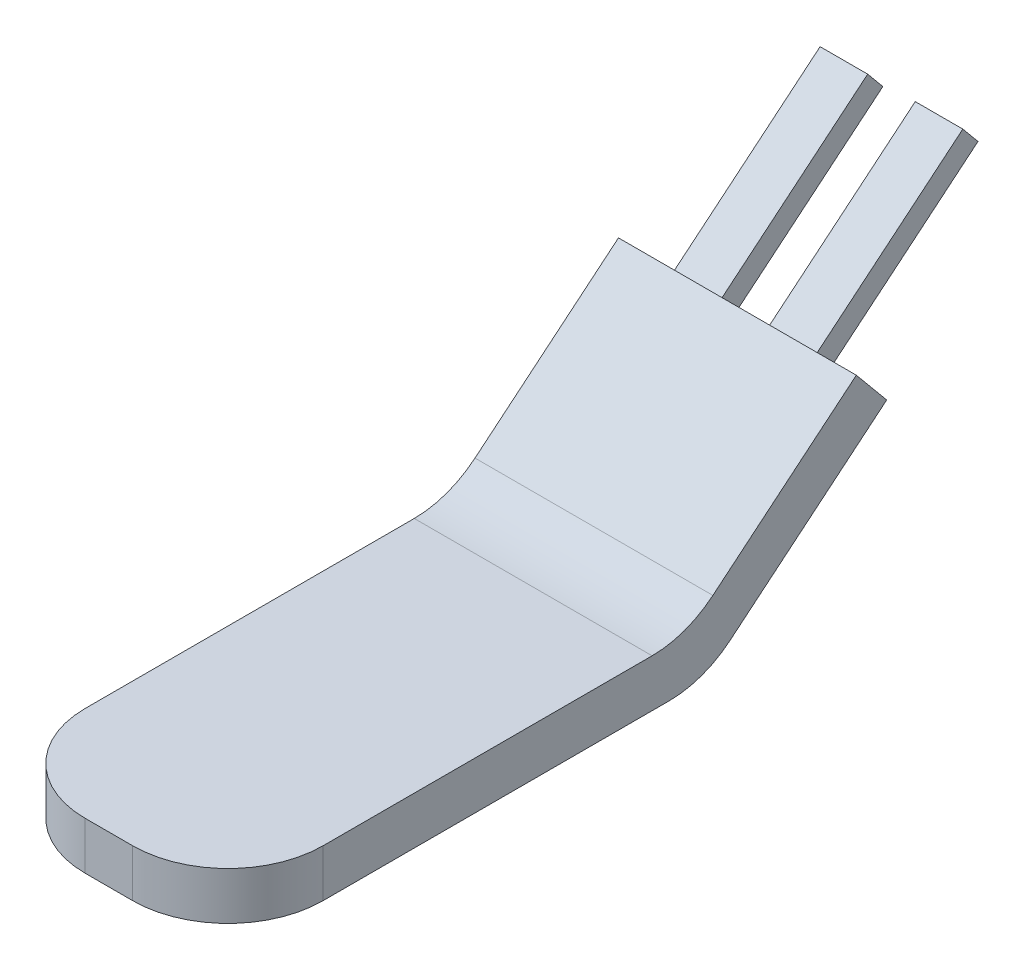
SolidWorks part; units mm, degrees
ref_plane "Front Plane" through (0, 0, 0) normal (0, 0, 1) x (1, 0, 0)
ref_plane "Top Plane" through (0, 0, 0) normal (0, 1, 0) x (1, 0, 0)
ref_plane "Right Plane" through (0, 0, 0) normal (1, 0, 0) x (0, 0, -1)
sketch "Sketch1" plane through (0, 0, 0) normal (1, 0, 0) x (0, 0, -1)
  line L0 (0, 0) -> (5, 0)
  line L1 (5, 0) -> (6.9242, 1.596)
  line L2 (6.9242, 1.596) -> (6.605, 1.9809)
  line L3 (6.605, 1.9809) -> (4.8196, 0.5)
  line L4 (4.8196, 0.5) -> (0, 0.5)
  line L5 (0, 0.5) -> (0, 0)
  dimension "D1" = 0.5
  dimension "D2" = 0.5
  dimension "D3" = 5
  dimension "D4" = 2.5
extrude "Boss-Extrude1" add sketch "Sketch1" along normal blind 2.5
fillet "Fillet1" radius 1 2 edges at (2.5, 0.25, 0) (0, 0.25, 0)
fillet "Fillet2" radius 1 2 edges at (1.25, 0, -5) (1.25, 0.5, -4.8196)
sketch "Sketch3" plane through (0, 4.0529, -4.8864) normal (0, 0.6384, -0.7697) x (-1, 0, 0)
  line L0 (-2.5, -2.9421) -> (0, -2.9421) construction
  line L1 (-2.5, -3.1921) -> (-2.5, -2.6921) construction
  line L2 (0, -3.1921) -> (0, -2.6921) construction
  line L4 (-1.5, -3.0671) -> (-2, -3.0671)
  line L5 (-1.5, -3.0671) -> (-1.5, -2.8171)
  line L6 (-1.5, -2.8171) -> (-2, -2.8171)
  line L7 (-2, -3.0671) -> (-2, -2.8171)
  line L8 (-1.5, -3.0671) -> (-2, -2.8171) construction
  line L9 (-1.5, -2.8171) -> (-2, -3.0671) construction
  line L10 (-1, -3.0671) -> (-0.5, -3.0671)
  line L11 (-1, -3.0671) -> (-1, -2.8171)
  line L12 (-1, -2.8171) -> (-0.5, -2.8171)
  line L13 (-0.5, -3.0671) -> (-0.5, -2.8171)
  line L14 (-1, -3.0671) -> (-0.5, -2.8171) construction
  line L15 (-1, -2.8171) -> (-0.5, -3.0671) construction
  point P6 (-1.75, -2.9421)
  point P11 (-0.75, -2.9421)
  point P16 (-1.25, -2.9421)
  dimension "D1" = 0.5
  dimension "D2" = 0.25
  dimension "D3" = 0.5
  dimension "D4" = 0.5
extrude "Boss-Extrude2" add sketch "Sketch3" along normal blind 2
